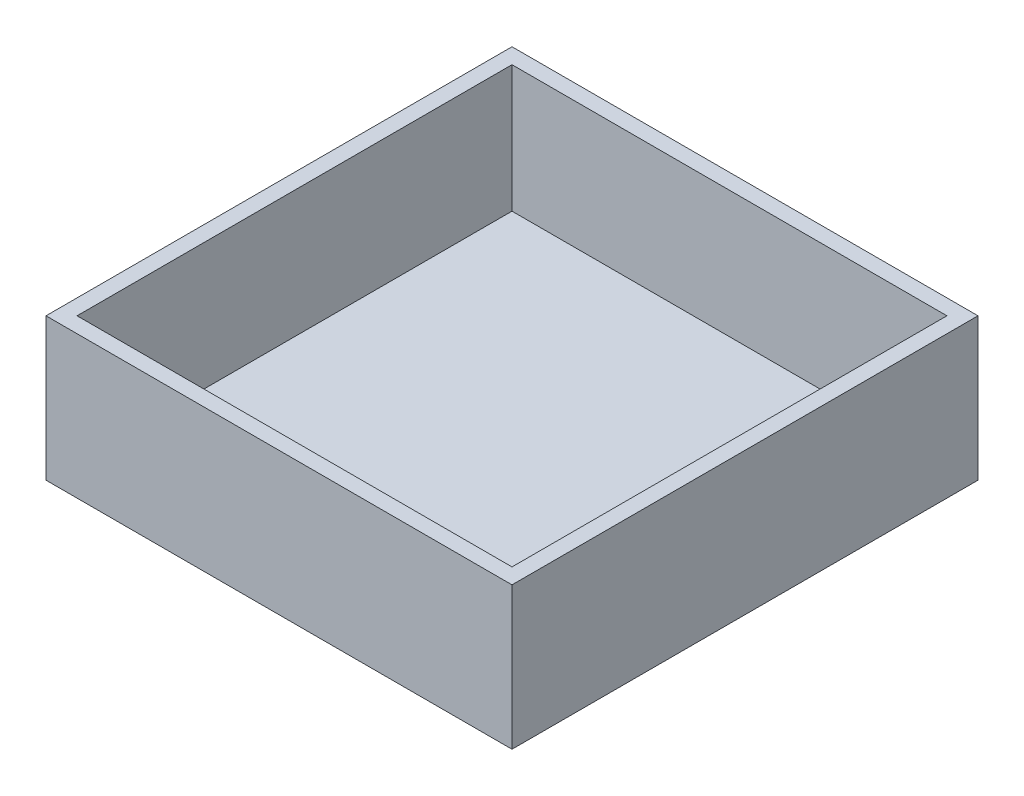
SolidWorks part; units mm, degrees
ref_plane "Front Plane" through (0, 0, 0) normal (0, 0, 1) x (1, 0, 0)
ref_plane "Top Plane" through (0, 0, 0) normal (0, 1, 0) x (1, 0, 0)
ref_plane "Right Plane" through (0, 0, 0) normal (1, 0, 0) x (0, 0, -1)
sketch "Sketch1" plane through (0, 0, 0) normal (0, 1, 0) x (1, 0, 0)
  line L1 (-45, -45) -> (45, -45)
  line L2 (-45, -45) -> (-45, 45)
  line L3 (-45, 45) -> (45, 45)
  line L4 (45, -45) -> (45, 45)
  line L5 (-45, -45) -> (45, 45) construction
  line L6 (-45, 45) -> (45, -45) construction
  point P0 (0, 0)
  dimension "D1" = 90
  dimension "D2" = 90
extrude "Boss-Extrude1" add sketch "Sketch1" along normal blind 27.5
sketch "Sketch2" plane through (0, 27.5, 0) normal (0, 1, 0) x (1, 0, 0)
  line L0 (-45, -45) -> (45, -45) construction
  line L1 (-42, -42) -> (42, -42)
  line L2 (-42, -42) -> (-42, 42)
  line L3 (-42, 42) -> (42, 42)
  line L4 (42, -42) -> (42, 42)
  line L5 (-42, -42) -> (42, 42) construction
  line L6 (-42, 42) -> (42, -42) construction
  line L7 (45, -45) -> (45, 45) construction
  point P0 (0, 0)
  dimension "D1" = 3
  dimension "D2" = 3
extrude "Cut-Extrude1" cut sketch "Sketch2" against normal offset from surface (24.5 mm away) 3 up to face at (0, 0, 0)
